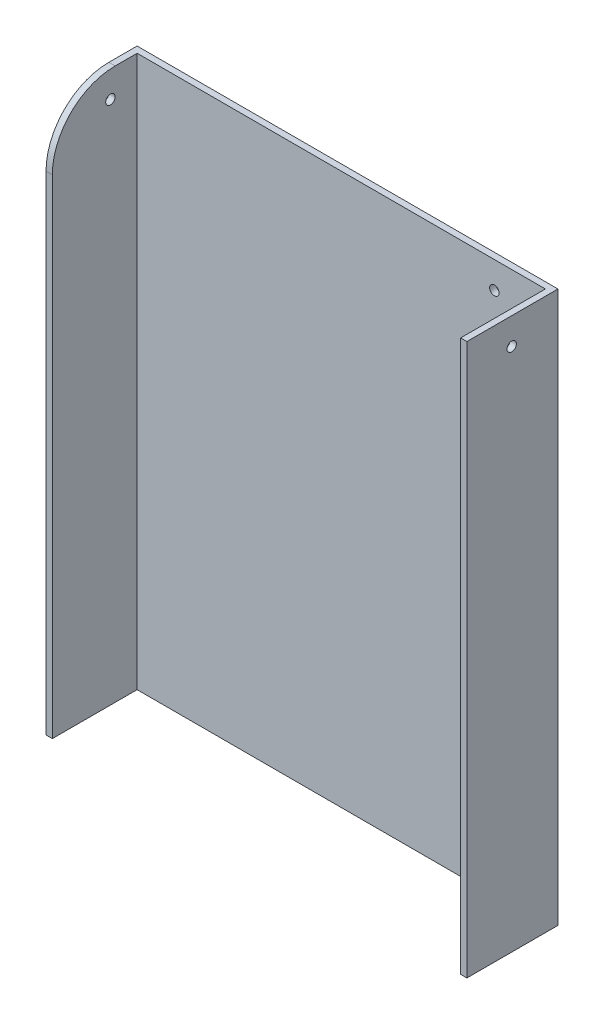
SolidWorks part; units mm, degrees
ref_plane "Front Plane" through (0, 0, 0) normal (0, 0, 1) x (1, 0, 0)
ref_plane "Top Plane" through (0, 0, 0) normal (0, 1, 0) x (1, 0, 0)
ref_plane "Right Plane" through (0, 0, 0) normal (1, 0, 0) x (0, 0, -1)
sketch "Sketch1" plane through (0, 0, 0) normal (0, 0, 1) x (1, 0, 0)
  line L1 (0, 0) -> (130, 0)
  line L2 (0, 0) -> (0, 175.5)
  line L3 (0, 175.5) -> (130, 175.5)
  line L4 (130, 0) -> (130, 175.5)
  dimension "D1" = 175.5
  dimension "D2" = 130
extrude "Boss-Extrude1" add sketch "Sketch1" along normal blind 2
sketch "Sketch2" plane through (130, 0, 0) normal (1, 0, 0) x (0, 0, -1)
  line L1 (0, 175.5) -> (-29, 175.5)
  line L2 (0, 175.5) -> (0, 0)
  line L3 (0, 0) -> (-29, 0)
  line L4 (-29, 175.5) -> (-29, 0)
  dimension "D1" = 29
extrude "Boss-Extrude2" add sketch "Sketch2" along normal blind 2
sketch "Sketch3" plane through (0, 0, 0) normal (-1, 0, 0) x (0, 0, 1)
  line L1 (0, 175.5) -> (29, 175.5)
  line L2 (0, 175.5) -> (0, 0)
  line L3 (0, 0) -> (29, 0)
  line L4 (29, 175.5) -> (29, 0)
  dimension "D1" = 29
extrude "Boss-Extrude3" add sketch "Sketch3" along normal blind 2
sketch "Sketch4" plane through (0, 0, 2) normal (0, 0, 1) x (1, 0, 0)
  line L0 (-2, 0) -> (132, 0) construction
  line L1 (115.3323, 5) -> (125.3323, 5)
  line L2 (115.3323, 5) -> (115.3323, 0)
  line L3 (115.3323, 0) -> (125.3323, 0)
  line L4 (125.3323, 5) -> (125.3323, 0)
  point P4 (120.3323, 0)
  dimension "D1" = 5
  dimension "D2" = 10
extrude "Cut-Extrude1" cut sketch "Sketch4" against normal blind 4
fillet "Fillet1" radius 20 1 edges at (-1, 175.5, 29)
fillet "Fillet2" radius 1 2 edges at (115.3323, 5, 1) (125.3323, 5, 1)
sketch "Sketch5" plane through (130, 0, 0) normal (-1, 0, 0) x (0, 0, 1)
  line L0 (2, 0) -> (2, 175.5) construction
  line L2 (2, 175.5) -> (29, 175.5) construction
  circle A0 centre (14.73, 167) radius 1.5
  point P6 (15.5001, 175.5)
  dimension "D1" = 3
  dimension "D2" = 12.73
  dimension "D3" = 8.5
extrude "Cut-Extrude2" cut sketch "Sketch5" against normal blind 2
sketch "Sketch6" plane through (0, 0, 2) normal (0, 0, 1) x (1, 0, 0)
  line L0 (130, 175.5) -> (0, 175.5) construction
  line L1 (130, 0) -> (130, 175.5) construction
  circle A0 centre (113.75, 167) radius 1.5
  point P6 (101.0108, 161.6138)
  dimension "D1" = 3
  dimension "D2" = 8.5
  dimension "D3" = 16.25
extrude "Cut-Extrude3" cut sketch "Sketch6" against normal blind 2
sketch "Sketch7" plane through (0, 0, 0) normal (1, 0, 0) x (0, 0, -1)
  line L0 (-2, 175.5) -> (-2, 0) construction
  line L1 (-9, 175.5) -> (-2, 175.5) construction
  circle A0 centre (-10.5, 167) radius 1.5
  point P6 (-5.5, 175.5)
  dimension "D1" = 3
  dimension "D2" = 8.5
  dimension "D3" = 8.5
extrude "Cut-Extrude4" cut sketch "Sketch7" against normal blind 2
